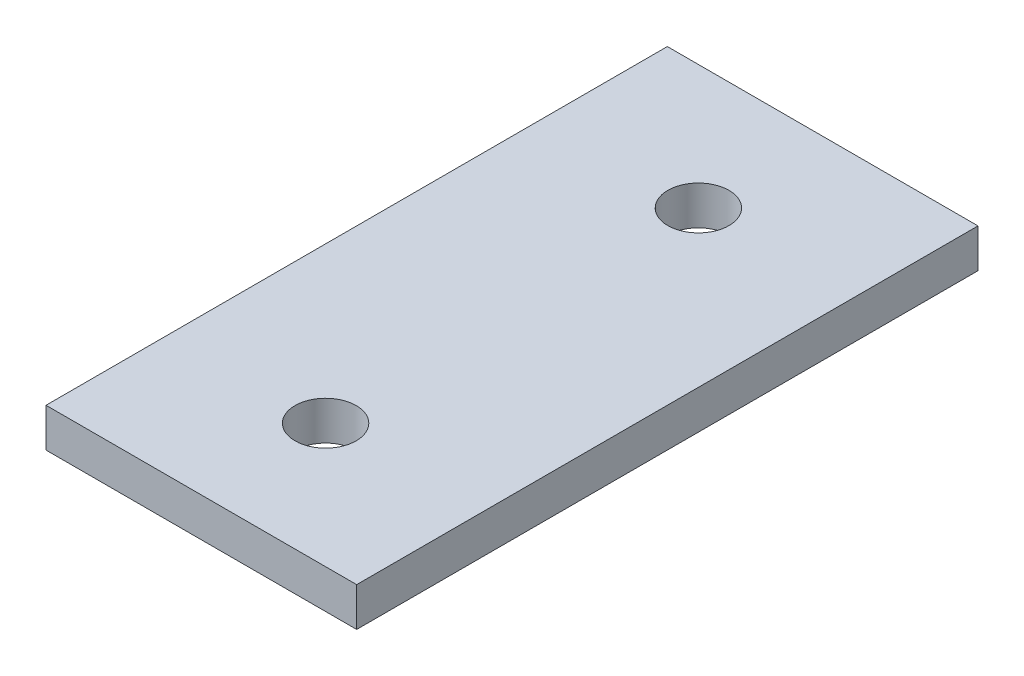
SolidWorks part; units mm, degrees
ref_plane "Front Plane" through (0, 0, 0) normal (0, 0, 1) x (1, 0, 0)
ref_plane "Top Plane" through (0, 0, 0) normal (0, 1, 0) x (1, 0, 0)
ref_plane "Right Plane" through (0, 0, 0) normal (1, 0, 0) x (0, 0, -1)
sketch "Sketch1" plane through (0, 0, 0) normal (0, 1, 0) x (1, 0, 0)
  line L0 (0, 0) -> (0, 25.4)
  line L1 (0, 25.4) -> (12.7, 25.4)
  line L2 (12.7, 25.4) -> (12.7, 0)
  line L3 (12.7, 0) -> (0, 0)
  point P5 (0, 0)
  dimension "D1" = 25.4
  dimension "D2" = 12.7
extrude "Boss-Extrude1" add sketch "Sketch1" along normal blind 1.5875
sketch "Sketch3" plane through (0, 1.5875, 0) normal (0, 1, 0) x (1, 0, 0)
  line L0 (12.7, 25.4) -> (0, 25.4) construction
  line L1 (12.7, 0) -> (12.7, 25.4) construction
  line L2 (0, 0) -> (12.7, 0) construction
  point P0 (6.35, 20.32)
  point P1 (6.35, 5.08)
  point P8 (0, 0)
  dimension "D1" = 5.08
  dimension "D2" = 6.35
  dimension "D3" = 5.08
hole_wizard "M3x0.5 Tapped Hole1" positions "Sketch4" profile "Sketch5" tap size "M3x0.5" standard "ANSI Metric" end condition through all
sketch "Sketch4" plane through (0, 1.5875, 0) normal (0, 1, 0) x (1, 0, 0)
  point P0 (6.35, 20.32)
  point P3 (6.35, 5.08)
sketch "Sketch5" plane through (6.35, 1.5875, -20.32) normal (1, 0, 0) x (0, 0, 1)
  line L0 (0, 0) -> (0, 1.5875)
  line L1 (0, 1.5875) -> (1.25, 1.5875)
  line L2 (1.25, 1.5875) -> (1.25, 0)
  line L5 (1.25, 0) -> (0, 0)
  line L11 (0, -6.35) -> (0, 107.95) construction
  dimension "Thru Tap Drill Dia." = 2.5
  dimension "Thru Tap Drill Depth" = 1.5875
cosmetic thread "Hole Thread1" parameters "D2"=3
cosmetic thread "Hole Thread2" parameters "D2"=3
